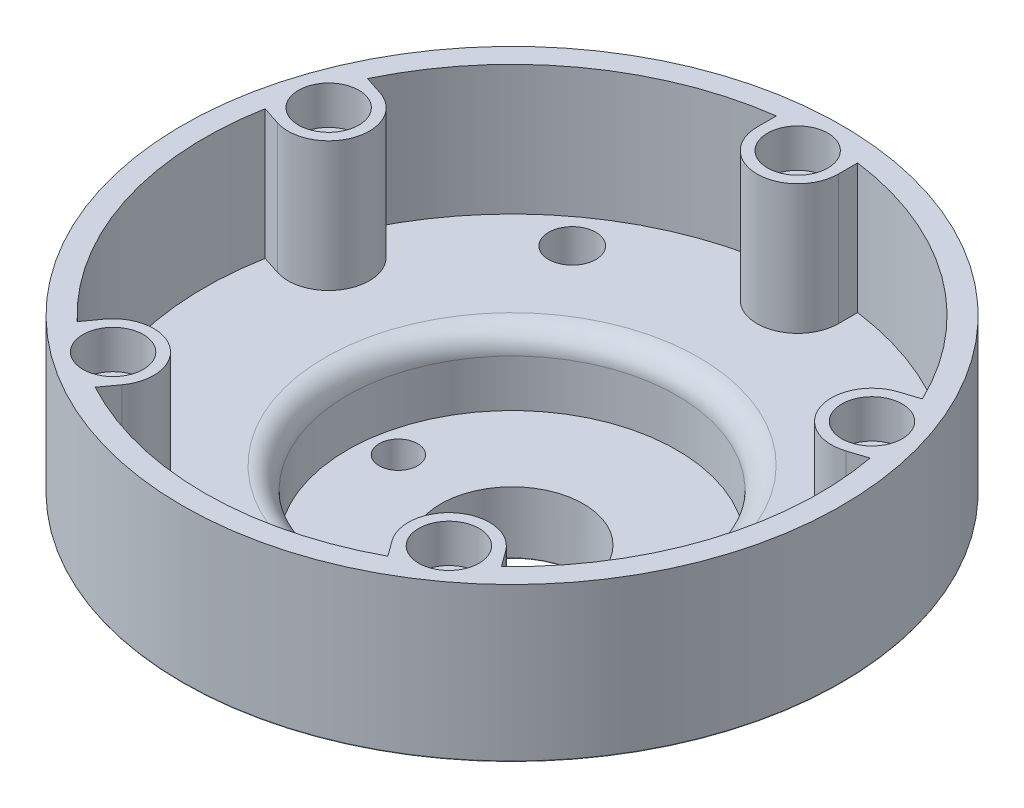
SolidWorks part; units mm, degrees
ref_plane "Front Plane" through (0, 0, 0) normal (0, 0, 1) x (1, 0, 0)
ref_plane "Top Plane" through (0, 0, 0) normal (0, 1, 0) x (1, 0, 0)
ref_plane "Right Plane" through (0, 0, 0) normal (1, 0, 0) x (0, 0, -1)
sketch "Sketch1" plane through (0, 0, 0) normal (0, 1, 0) x (1, 0, 0)
  circle A0 centre (0, 0) radius 30
extrude "Boss-Extrude1" add sketch "Sketch1" along normal blind 14
sketch "Sketch2" plane through (0, 0, 0) normal (0, -1, 0) x (1, 0, 0)
  circle A0 centre (0, 0) radius 16.125
extrude "Boss-Extrude2" add sketch "Sketch2" along normal blind 9.8
sketch "Sketch3" plane through (0, 14, 0) normal (0, 1, 0) x (1, 0, 0)
  line L0 (-3.7, 26) -> (-3.7, 27.7545)
  line L1 (3.7, 26) -> (3.7, 27.7545)
  line L2 (23.5841, 11.5534) -> (25.2527, 12.0955)
  line L3 (25.8708, 4.5155) -> (27.5394, 5.0577)
  line L4 (18.2758, -18.8596) -> (19.307, -20.279)
  line L5 (12.2891, -23.2092) -> (13.3203, -24.6286)
  line L6 (-12.2891, -23.2092) -> (-13.3203, -24.6286)
  line L7 (-18.2758, -18.8596) -> (-19.307, -20.279)
  line L8 (-25.8708, 4.5155) -> (-27.5394, 5.0577)
  line L9 (-23.5841, 11.5534) -> (-25.2527, 12.0955)
  arc A0 (-27.5394, 5.0577) -> (-19.307, -20.279) centre (0, 0) ccw
  circle A1 centre (0, 0) radius 22.3 construction
  arc A2 (-3.7, 26) -> (3.7, 26) centre (0, 26) ccw
  arc A3 (23.5841, 11.5534) -> (25.8708, 4.5155) centre (24.7275, 8.0344) ccw
  arc A4 (18.2758, -18.8596) -> (12.2891, -23.2092) centre (15.2824, -21.0344) ccw
  arc A5 (-12.2891, -23.2092) -> (-18.2758, -18.8596) centre (-15.2824, -21.0344) ccw
  arc A6 (-25.8708, 4.5155) -> (-23.5841, 11.5534) centre (-24.7275, 8.0344) ccw
  arc A7 (-3.7, 27.7545) -> (-25.2527, 12.0955) centre (0, 0) ccw
  arc A8 (25.2527, 12.0955) -> (3.7, 27.7545) centre (0, 0) ccw
  arc A9 (19.307, -20.279) -> (27.5394, 5.0577) centre (0, 0) ccw
  arc A10 (-13.3203, -24.6286) -> (13.3203, -24.6286) centre (0, 0) ccw
  point P36 (0, 0)
  dimension "D1" = 5
extrude "Cut-Extrude1" cut sketch "Sketch3" against normal blind 11.8
sketch "Sketch4" plane through (0, 2.2, 0) normal (0, 1, 0) x (1, 0, 0)
  circle A0 centre (0, 0) radius 15
extrude "Cut-Extrude2" cut sketch "Sketch4" against normal blind 6.3
sketch "Sketch5" plane through (0, -4.1, 0) normal (0, 1, 0) x (1, 0, 0)
  circle A0 centre (0, 0) radius 6.5
extrude "Cut-Extrude3" cut sketch "Sketch5" against normal blind 8.3
sketch "Sketch6" plane through (0, 14, 0) normal (0, 1, 0) x (1, 0, 0)
  circle A0 centre (0, 26) radius 2.75
  circle A1 centre (24.7275, 8.0344) radius 2.75
  circle A2 centre (15.2824, -21.0344) radius 2.75
  circle A3 centre (-15.2824, -21.0344) radius 2.75
  circle A4 centre (-24.7275, 8.0344) radius 2.75
  point P13 (0, 0)
  dimension "D1" = 5
extrude "Cut-Extrude4" cut sketch "Sketch6" against normal blind 3.5
sketch "Sketch7" plane through (0, 10.5, 0) normal (0, 1, 0) x (1, 0, 0)
  circle A0 centre (15.2824, -21.0344) radius 1.25
  circle A1 centre (-15.2824, -21.0344) radius 1.25
  circle A2 centre (-24.7275, 8.0344) radius 1.25
  circle A3 centre (0, 26) radius 1.25
  circle A4 centre (24.7275, 8.0344) radius 1.25
  point P13 (0, 0)
  dimension "D1" = 5
extrude "Cut-Extrude5" cut sketch "Sketch7" against normal through all
sketch "Sketch8" plane through (0, -4.1, 0) normal (0, 1, 0) x (1, 0, 0)
  circle A0 centre (0, 0) radius 12.45 construction
  circle A1 centre (-12.2967, 1.9476) radius 1.75
  circle A2 centre (12.2967, -1.9476) radius 1.75
extrude "Cut-Extrude6" cut sketch "Sketch8" against normal through all
sketch "Sketch10" plane through (0, 0, 0) normal (0, -1, 0) x (1, 0, 0)
  arc A1 (-23.5386, -7.6482) -> (0, -24.75) centre (0, 0) ccw construction
  circle A6 centre (-14.5477, -20.0232) radius 3.25
extrude "Boss-Extrude3" add sketch "Sketch10" along normal up to surface (9.8 mm away) up to face at (-12.2967, -9.8, -0.1976)
sketch "Sketch11" plane through (0, -9.8, 0) normal (0, -1, 0) x (1, 0, 0)
  circle A0 centre (-14.5477, -20.0232) radius 2.15
extrude "Cut-Extrude7" cut sketch "Sketch11" against normal through all
fillet "Fillet1" radius 2 1 edges at (0, 2.2, 15)
chamfer "Chamfer1" distance 1 angle 45 1 edges at (-14.5477, 0, -16.7732)
fillet "Fillet2" radius 0.1 3 edges at (0, -9.8, -16.125) (0, 0, 30) (0, -9.8, -6.5)
fillet "Fillet3" radius 0.4 2 edges at (-14.5477, -9.8, -22.1732) (-14.5477, -9.8, -23.2732)
fillet "Fillet4" radius 1 1 edges at (0, 0, -16.125)
